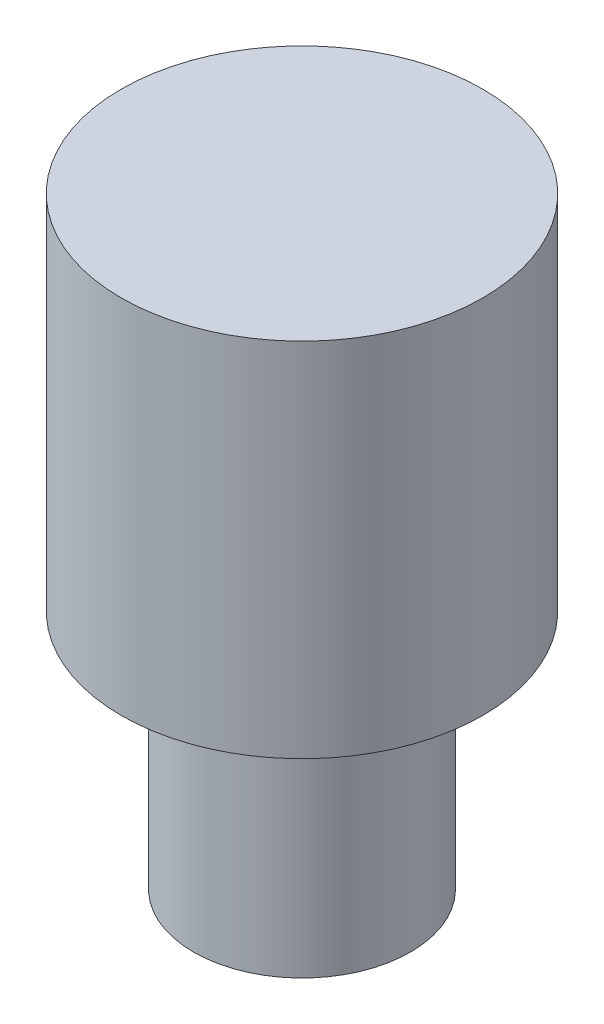
SolidWorks part; units mm, degrees
ref_plane "前视基准面" through (0, 0, 0) normal (0, 0, 1) x (1, 0, 0)
ref_plane "上视基准面" through (0, 0, 0) normal (0, 1, 0) x (1, 0, 0)
ref_plane "右视基准面" through (0, 0, 0) normal (1, 0, 0) x (0, 0, -1)
other "Configuration Table"
sketch "草图1" plane through (0, 0, 0) normal (0, 1, 0) x (1, 0, 0)
  line L0 (-32.2336, 0) -> (32.7664, 0)
  line L1 (0, -63.8232) -> (0, 21.1768)
  circle A0 centre (0, 0) radius 9
  dimension "D1" = 18
  dimension "D2" = 85
  dimension "D3" = 65
extrude "凸台-拉伸1" add sketch "草图1" along normal blind 20 contours A0
sketch "草图2" plane through (0, 20, 0) normal (0, 1, 0) x (1, 0, 0)
  circle A0 centre (0, 0) radius 15
  circle A1 centre (0, 0) radius 9
  circle A2 centre (0, 0) radius 9
  dimension "D2" = 30
  dimension "D1" = 0
extrude "凸台-拉伸3" add sketch "草图2" along normal blind 30 separate body contours A0
